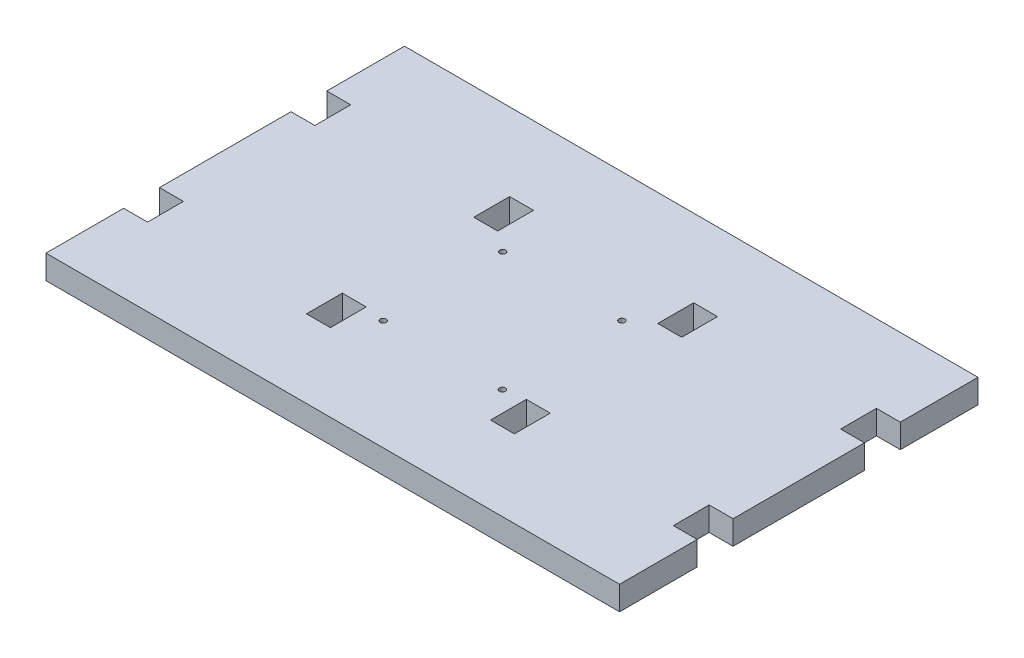
SolidWorks part; units mm, degrees
material "Acrylic (Medium-high impact)"
ref_plane "Front Plane" through (0, 0, 0) normal (0, 0, 1) x (1, 0, 0)
ref_plane "Top Plane" through (0, 0, 0) normal (0, 1, 0) x (1, 0, 0)
ref_plane "Right Plane" through (0, 0, 0) normal (1, 0, 0) x (0, 0, -1)
sketch "Sketch1" plane through (0, 0, 0) normal (0, 1, 0) x (1, 0, 0)
  line L1 (-152.4, 95.25) -> (152.4, 95.25)
  line L2 (-152.4, 95.25) -> (-152.4, -95.25)
  line L3 (-152.4, -95.25) -> (152.4, -95.25)
  line L4 (152.4, 95.25) -> (152.4, -95.25)
  line L5 (-152.4, 95.25) -> (152.4, -95.25) construction
  line L6 (-152.4, -95.25) -> (152.4, 95.25) construction
  point P0 (0, 0)
  dimension "D1" = 190.5
  dimension "D2" = 304.8
extrude "Extrude1" add sketch "Sketch1" along normal blind 12.7
sketch "Sketch2" plane through (0, 12.7, 0) normal (0, 1, 0) x (1, 0, 0)
  line L0 (0, 0) -> (0, 93.8784) construction
  line L1 (0, 0) -> (156.2405, 0) construction
  line L2 (-55.245, 53.975) -> (-55.245, 34.925)
  line L3 (42.545, 53.975) -> (55.245, 53.975)
  line L4 (42.545, 53.975) -> (42.545, 34.925)
  line L5 (42.545, 34.925) -> (55.245, 34.925)
  line L6 (55.245, 53.975) -> (55.245, 34.925)
  line L7 (-42.545, 34.925) -> (-55.245, 34.925)
  line L8 (-42.545, 53.975) -> (-42.545, 34.925)
  line L9 (-42.545, 53.975) -> (-55.245, 53.975)
  line L10 (-42.545, -53.975) -> (-55.245, -53.975)
  line L11 (-42.545, -53.975) -> (-42.545, -34.925)
  line L12 (-42.545, -34.925) -> (-55.245, -34.925)
  line L13 (55.245, -53.975) -> (55.245, -34.925)
  line L14 (42.545, -34.925) -> (55.245, -34.925)
  line L15 (42.545, -53.975) -> (42.545, -34.925)
  line L16 (42.545, -53.975) -> (55.245, -53.975)
  line L17 (-55.245, -53.975) -> (-55.245, -34.925)
  line L18 (152.4, -95.25) -> (152.4, 95.25) construction
  line L19 (152.4, 53.975) -> (139.7, 53.975)
  line L20 (152.4, 53.975) -> (152.4, 34.925)
  line L21 (152.4, 34.925) -> (139.7, 34.925)
  line L22 (139.7, 53.975) -> (139.7, 34.925)
  line L23 (-139.7, 53.975) -> (-139.7, 34.925)
  line L24 (-152.4, 34.925) -> (-139.7, 34.925)
  line L25 (-152.4, 53.975) -> (-152.4, 34.925)
  line L26 (-152.4, 53.975) -> (-139.7, 53.975)
  line L27 (139.7, -53.975) -> (139.7, -34.925)
  line L28 (152.4, -34.925) -> (139.7, -34.925)
  line L29 (152.4, -53.975) -> (152.4, -34.925)
  line L30 (152.4, -53.975) -> (139.7, -53.975)
  line L31 (-152.4, -53.975) -> (-139.7, -53.975)
  line L32 (-152.4, -53.975) -> (-152.4, -34.925)
  line L33 (-152.4, -34.925) -> (-139.7, -34.925)
  line L34 (-139.7, -53.975) -> (-139.7, -34.925)
  dimension "D1" = 19.05
  dimension "D2" = 12.7
  dimension "D3" = 42.545
  dimension "D4" = 34.925
extrude "Extrude2" cut sketch "Sketch2" against normal through all
sketch "Sketch3" plane through (0, 0, 0) normal (0, -1, 0) x (1, 0, 0)
  line L0 (34.8615, 43.1462) -> (34.8615, 30.4462) construction
  line L1 (34.8615, -20.3538) -> (34.8615, -33.0538) construction
  line L2 (0, 0) -> (0, 49.2523) construction
  circle A0 centre (31.6865, 36.7962) radius 1.5875
  circle A1 centre (31.6865, -26.7038) radius 1.5875
  circle A3 centre (-31.6865, -26.7038) radius 1.5875
  circle A4 centre (-31.6865, 36.7962) radius 1.5875
  point P6 (34.8615, 36.7962)
  point P9 (34.8615, -26.7038)
  point P13 (31.6865, 43.1462)
  point P19 (-31.6865, 43.1462)
  dimension "D1" = 3.175
extrude "Cut-Extrude1" cut sketch "Sketch3" against normal through all
